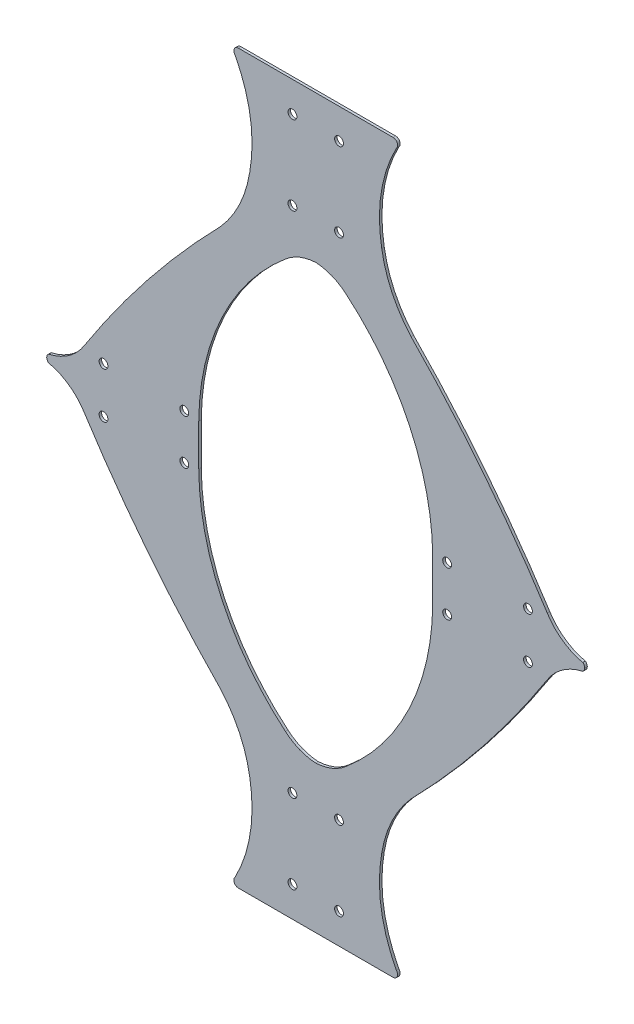
SolidWorks part; units mm, degrees
ref_plane "Front Plane" through (0, 0, 0) normal (0, 0, 1) x (1, 0, 0)
ref_plane "Top Plane" through (0, 0, 0) normal (0, 1, 0) x (1, 0, 0)
ref_plane "Right Plane" through (0, 0, 0) normal (1, 0, 0) x (0, 0, -1)
sketch "Model" plane through (0, 0, 0) normal (0, 0, 1) x (1, 0, 0)
  line B0 (293.8436, -56.5322) -> (293.8436, 0)
  line B1 (0, 914.4) -> (194.4798, 914.4)
  line B2 (293.8436, 56.5322) -> (293.8436, 0)
  line B3 (0, 914.4) -> (-194.4798, 914.4)
  line B4 (0, 545.0832) -> (0, 0) construction
  line B5 (0, 0) -> (293.8436, 0) construction
  arc B6 (239.6834, -503.1053) -> (187.9198, -583.3951) centre (465.825, -705.7322) ccw
  arc B7 (239.6834, -503.1053) -> (582.0374, -72.7477) centre (-1699.953, 1391.2476) ccw
  arc B8 (671.3071, -9.5736) -> (582.0374, -72.7477) centre (702.2766, -147.9952) ccw
  arc B9 (671.3071, -9.5736) -> (676.2743, 0) centre (664.8452, -0.1455) ccw
  arc B10 (101.6984, -491.6043) -> (294.1166, -52.0761) centre (-316.104, -46.8144) ccw
  circle B11 centre (330.3561, -56.5322) radius 11.1125
  circle B12 centre (533.5906, -57.7678) radius 11.1125
  arc B13 (202.9832, 895.3321) -> (194.4798, 914.4) centre (194.4798, 902.97) ccw
  arc B14 (202.9832, 895.3321) -> (165.892, 658.247) centre (527.5303, 723.1138) ccw
  arc B15 (165.9389, 658.1298) -> (239.6834, 503.1053) centre (465.825, 705.7322) ccw
  arc B16 (582.0374, 72.7477) -> (239.6834, 503.1053) centre (-1699.953, -1391.2476) ccw
  arc B17 (582.0374, 72.7477) -> (671.3071, 9.5736) centre (702.2766, 147.9952) ccw
  arc B18 (676.2743, 0) -> (671.3071, 9.5736) centre (664.8452, 0.1455) ccw
  arc B19 (294.1166, 52.0761) -> (76.1318, 514.3055) centre (-316.104, 46.8144) ccw
  arc B20 (76.1318, 514.3055) -> (0, 545.0832) centre (-7, 418.2194) ccw
  circle B21 centre (58.5418, 838.2689) radius 11.1125
  circle B22 centre (330.3561, 56.5322) radius 11.1125
  circle B23 centre (533.5906, 57.7678) radius 11.1125
  circle B24 centre (58.5418, 639.4053) radius 11.1125
  arc B25 (-194.4798, 914.4) -> (-202.9832, 895.3321) centre (-194.4798, 902.97) ccw
  arc B26 (-165.892, 658.247) -> (-202.9832, 895.3321) centre (-527.5303, 723.1138) ccw
  arc B27 (-187.9198, 583.3951) -> (-165.9389, 658.1298) centre (-465.825, 705.7322) ccw
  arc B28 (-76.1318, 514.3055) -> (-101.6984, 491.6043) centre (316.104, 46.8144) ccw
  arc B29 (0, 545.0832) -> (-76.1318, 514.3055) centre (7, 418.2194) ccw
  circle B30 centre (-58.5418, 838.2689) radius 11.1125
  circle B31 centre (-58.5418, 639.4053) radius 11.1125
  line B32 (-293.8436, 56.5322) -> (-293.8436, 0)
  line B33 (0, -914.4) -> (-194.4798, -914.4)
  line B34 (-293.8436, -56.5322) -> (-293.8436, 0)
  line B35 (0, -914.4) -> (194.4798, -914.4)
  line B36 (0, -545.0832) -> (0, 0) construction
  line B37 (0, 0) -> (-293.8436, 0) construction
  arc B38 (-239.6834, 503.1053) -> (-187.9198, 583.3951) centre (-465.825, 705.7322) ccw
  arc B39 (-239.6834, 503.1053) -> (-582.0374, 72.7477) centre (1699.953, -1391.2476) ccw
  arc B40 (-671.3071, 9.5736) -> (-582.0374, 72.7477) centre (-702.2766, 147.9952) ccw
  arc B41 (-671.3071, 9.5736) -> (-676.2743, 0) centre (-664.8452, 0.1455) ccw
  arc B42 (-101.6984, 491.6043) -> (-294.1166, 52.0761) centre (316.104, 46.8144) ccw
  circle B43 centre (-330.3561, 56.5322) radius 11.1125
  circle B44 centre (-533.5906, 57.7678) radius 11.1125
  arc B45 (-202.9832, -895.3321) -> (-194.4798, -914.4) centre (-194.4798, -902.97) ccw
  arc B46 (-202.9832, -895.3321) -> (-165.892, -658.247) centre (-527.5303, -723.1138) ccw
  arc B47 (-165.9389, -658.1298) -> (-239.6834, -503.1053) centre (-465.825, -705.7322) ccw
  arc B48 (-582.0374, -72.7477) -> (-239.6834, -503.1053) centre (1699.953, 1391.2476) ccw
  arc B49 (-582.0374, -72.7477) -> (-671.3071, -9.5736) centre (-702.2766, -147.9952) ccw
  arc B50 (-676.2743, 0) -> (-671.3071, -9.5736) centre (-664.8452, -0.1455) ccw
  arc B51 (-294.1166, -52.0761) -> (-76.1318, -514.3055) centre (316.104, -46.8144) ccw
  arc B52 (-76.1318, -514.3055) -> (0, -545.0832) centre (7, -418.2194) ccw
  circle B53 centre (-58.5418, -838.2689) radius 11.1125
  circle B54 centre (-330.3561, -56.5322) radius 11.1125
  circle B55 centre (-533.5906, -57.7678) radius 11.1125
  circle B56 centre (-58.5418, -639.4053) radius 11.1125
  arc B57 (194.4798, -914.4) -> (202.9832, -895.3321) centre (194.4798, -902.97) ccw
  arc B58 (165.892, -658.247) -> (202.9832, -895.3321) centre (527.5303, -723.1138) ccw
  arc B59 (187.9198, -583.3951) -> (165.9389, -658.1298) centre (465.825, -705.7322) ccw
  arc B60 (76.1318, -514.3055) -> (101.6984, -491.6043) centre (-316.104, -46.8144) ccw
  arc B61 (0, -545.0832) -> (76.1318, -514.3055) centre (-7, -418.2194) ccw
  circle B62 centre (58.5418, -838.2689) radius 11.1125
  circle B63 centre (58.5418, -639.4053) radius 11.1125
sketch_block_instance "Block1-1"
sketch_block "Block1"
sketch_block_instance "Block1-2"
sketch "Sketch2" plane through (0, 0, 0) normal (0, 0, 1) x (1, 0, 0)
  line L0 (0, 914.4) -> (-194.4798, 914.4) construction
  line L1 (0, 914.4) -> (194.4798, 914.4) construction
  line L2 (0, -914.4) -> (-194.4798, -914.4) construction
  line L3 (0, -914.4) -> (194.4798, -914.4) construction
  line L4 (0, 914.4) -> (-194.4798, 914.4)
  line L5 (0, 914.4) -> (194.4798, 914.4)
  line L6 (0, -914.4) -> (-194.4798, -914.4)
  line L7 (0, -914.4) -> (194.4798, -914.4)
  line L8 (294.1166, 52.0761) -> (294.1166, -52.0761)
  line L9 (-294.1166, -52.0761) -> (-294.1166, 52.0761)
  line L10 (-165.9389, 658.1298) -> (-165.892, 658.247)
  line L11 (165.892, 658.247) -> (165.9389, 658.1298)
  line L12 (165.892, -658.247) -> (165.9389, -658.1298)
  line L13 (-165.892, -658.247) -> (-165.9389, -658.1298)
  arc A0 (582.0374, 72.7477) -> (239.6834, 503.1053) centre (-1699.953, -1391.2476) ccw construction
  arc A1 (165.9389, 658.1298) -> (239.6834, 503.1053) centre (465.825, 705.7322) ccw construction
  arc A2 (202.9832, 895.3321) -> (165.892, 658.247) centre (527.5303, 723.1138) ccw construction
  arc A3 (202.9832, 895.3321) -> (194.4798, 914.4) centre (194.4798, 902.97) ccw construction
  arc A4 (-194.4798, 914.4) -> (-202.9832, 895.3321) centre (-194.4798, 902.97) ccw construction
  arc A5 (-165.892, 658.247) -> (-202.9832, 895.3321) centre (-527.5303, 723.1138) ccw construction
  arc A6 (-187.9198, 583.3951) -> (-165.9389, 658.1298) centre (-465.825, 705.7322) ccw construction
  arc A7 (-239.6834, 503.1053) -> (-187.9198, 583.3951) centre (-465.825, 705.7322) ccw construction
  arc A8 (-239.6834, 503.1053) -> (-582.0374, 72.7477) centre (1699.953, -1391.2476) ccw construction
  arc A9 (-671.3071, 9.5736) -> (-582.0374, 72.7477) centre (-702.2766, 147.9952) ccw construction
  arc A10 (-671.3071, 9.5736) -> (-676.2743, 0) centre (-664.8452, 0.1455) ccw construction
  arc A11 (-676.2743, 0) -> (-671.3071, -9.5736) centre (-664.8452, -0.1455) ccw construction
  arc A12 (-582.0374, -72.7477) -> (-671.3071, -9.5736) centre (-702.2766, -147.9952) ccw construction
  arc A13 (-582.0374, -72.7477) -> (-239.6834, -503.1053) centre (1699.953, 1391.2476) ccw construction
  arc A14 (-165.9389, -658.1298) -> (-239.6834, -503.1053) centre (-465.825, -705.7322) ccw construction
  arc A15 (-202.9832, -895.3321) -> (-165.892, -658.247) centre (-527.5303, -723.1138) ccw construction
  arc A16 (-202.9832, -895.3321) -> (-194.4798, -914.4) centre (-194.4798, -902.97) ccw construction
  arc A17 (194.4798, -914.4) -> (202.9832, -895.3321) centre (194.4798, -902.97) ccw construction
  arc A18 (165.892, -658.247) -> (202.9832, -895.3321) centre (527.5303, -723.1138) ccw construction
  arc A19 (187.9198, -583.3951) -> (165.9389, -658.1298) centre (465.825, -705.7322) ccw construction
  arc A20 (239.6834, -503.1053) -> (187.9198, -583.3951) centre (465.825, -705.7322) ccw construction
  arc A21 (239.6834, -503.1053) -> (582.0374, -72.7477) centre (-1699.953, 1391.2476) ccw construction
  arc A22 (582.0374, 72.7477) -> (671.3071, 9.5736) centre (702.2766, 147.9952) ccw construction
  arc A23 (676.2743, 0) -> (671.3071, 9.5736) centre (664.8452, 0.1455) ccw construction
  arc A24 (671.3071, -9.5736) -> (676.2743, 0) centre (664.8452, -0.1455) ccw construction
  arc A25 (671.3071, -9.5736) -> (582.0374, -72.7477) centre (702.2766, -147.9952) ccw construction
  arc A26 (-294.1166, -52.0761) -> (-76.1318, -514.3055) centre (316.104, -46.8144) ccw construction
  arc A27 (-101.6984, 491.6043) -> (-294.1166, 52.0761) centre (316.104, 46.8144) ccw construction
  arc A28 (-76.1318, 514.3055) -> (-101.6984, 491.6043) centre (316.104, 46.8144) ccw construction
  arc A29 (0, 545.0832) -> (-76.1318, 514.3055) centre (7, 418.2194) ccw construction
  arc A30 (76.1318, 514.3055) -> (0, 545.0832) centre (-7, 418.2194) ccw construction
  arc A31 (294.1166, 52.0761) -> (76.1318, 514.3055) centre (-316.104, 46.8144) ccw construction
  arc A32 (101.6984, -491.6043) -> (294.1166, -52.0761) centre (-316.104, -46.8144) ccw construction
  arc A33 (0, -545.0832) -> (76.1318, -514.3055) centre (-7, -418.2194) ccw construction
  arc A34 (-76.1318, -514.3055) -> (0, -545.0832) centre (7, -418.2194) ccw construction
  arc A35 (76.1318, -514.3055) -> (101.6984, -491.6043) centre (-316.104, -46.8144) ccw construction
  circle A36 centre (-58.5418, -639.4053) radius 11.1125 construction
  circle A37 centre (-58.5418, -838.2689) radius 11.1125 construction
  circle A38 centre (58.5418, -838.2689) radius 11.1125 construction
  circle A39 centre (58.5418, -639.4053) radius 11.1125 construction
  circle A40 centre (533.5906, -57.7678) radius 11.1125 construction
  circle A41 centre (330.3561, -56.5322) radius 11.1125 construction
  circle A42 centre (330.3561, 56.5322) radius 11.1125 construction
  circle A43 centre (533.5906, 57.7678) radius 11.1125 construction
  circle A44 centre (58.5418, 838.2689) radius 11.1125 construction
  circle A45 centre (-58.5418, 838.2689) radius 11.1125 construction
  circle A46 centre (-58.5418, 639.4053) radius 11.1125 construction
  circle A47 centre (58.5418, 639.4053) radius 11.1125 construction
  circle A48 centre (-330.3561, -56.5322) radius 11.1125 construction
  circle A49 centre (-330.3561, 56.5322) radius 11.1125 construction
  circle A50 centre (-533.5906, 57.7678) radius 11.1125 construction
  circle A51 centre (-533.5906, -57.7678) radius 11.1125 construction
  arc A52 (582.0374, 72.7477) -> (239.6834, 503.1053) centre (-1699.953, -1391.2476) ccw
  arc A53 (165.9389, 658.1298) -> (239.6834, 503.1053) centre (465.825, 705.7322) ccw
  arc A54 (202.9832, 895.3321) -> (165.892, 658.247) centre (527.5303, 723.1138) ccw
  arc A55 (202.9832, 895.3321) -> (194.4798, 914.4) centre (194.4798, 902.97) ccw
  arc A56 (-194.4798, 914.4) -> (-202.9832, 895.3321) centre (-194.4798, 902.97) ccw
  arc A57 (-165.892, 658.247) -> (-202.9832, 895.3321) centre (-527.5303, 723.1138) ccw
  arc A58 (-187.9198, 583.3951) -> (-165.9389, 658.1298) centre (-465.825, 705.7322) ccw
  arc A59 (-239.6834, 503.1053) -> (-187.9198, 583.3951) centre (-465.825, 705.7322) ccw
  arc A60 (-239.6834, 503.1053) -> (-582.0374, 72.7477) centre (1699.953, -1391.2476) ccw
  arc A61 (-671.3071, 9.5736) -> (-582.0374, 72.7477) centre (-702.2766, 147.9952) ccw
  arc A62 (-671.3071, 9.5736) -> (-676.2743, 0) centre (-664.8452, 0.1455) ccw
  arc A63 (-676.2743, 0) -> (-671.3071, -9.5736) centre (-664.8452, -0.1455) ccw
  arc A64 (-582.0374, -72.7477) -> (-671.3071, -9.5736) centre (-702.2766, -147.9952) ccw
  arc A65 (-582.0374, -72.7477) -> (-239.6834, -503.1053) centre (1699.953, 1391.2476) ccw
  arc A66 (-165.9389, -658.1298) -> (-239.6834, -503.1053) centre (-465.825, -705.7322) ccw
  arc A67 (-202.9832, -895.3321) -> (-165.892, -658.247) centre (-527.5303, -723.1138) ccw
  arc A68 (-202.9832, -895.3321) -> (-194.4798, -914.4) centre (-194.4798, -902.97) ccw
  arc A69 (194.4798, -914.4) -> (202.9832, -895.3321) centre (194.4798, -902.97) ccw
  arc A70 (165.892, -658.247) -> (202.9832, -895.3321) centre (527.5303, -723.1138) ccw
  arc A71 (187.9198, -583.3951) -> (165.9389, -658.1298) centre (465.825, -705.7322) ccw
  arc A72 (239.6834, -503.1053) -> (187.9198, -583.3951) centre (465.825, -705.7322) ccw
  arc A73 (239.6834, -503.1053) -> (582.0374, -72.7477) centre (-1699.953, 1391.2476) ccw
  arc A74 (582.0374, 72.7477) -> (671.3071, 9.5736) centre (702.2766, 147.9952) ccw
  arc A75 (676.2743, 0) -> (671.3071, 9.5736) centre (664.8452, 0.1455) ccw
  arc A76 (671.3071, -9.5736) -> (676.2743, 0) centre (664.8452, -0.1455) ccw
  arc A77 (671.3071, -9.5736) -> (582.0374, -72.7477) centre (702.2766, -147.9952) ccw
  arc A78 (-294.1166, -52.0761) -> (-76.1318, -514.3055) centre (316.104, -46.8144) ccw
  arc A79 (-101.6984, 491.6043) -> (-294.1166, 52.0761) centre (316.104, 46.8144) ccw
  arc A80 (-76.1318, 514.3055) -> (-101.6984, 491.6043) centre (316.104, 46.8144) ccw
  arc A81 (0, 545.0832) -> (-76.1318, 514.3055) centre (7, 418.2194) ccw
  arc A82 (76.1318, 514.3055) -> (0, 545.0832) centre (-7, 418.2194) ccw
  arc A83 (294.1166, 52.0761) -> (76.1318, 514.3055) centre (-316.104, 46.8144) ccw
  arc A84 (101.6984, -491.6043) -> (294.1166, -52.0761) centre (-316.104, -46.8144) ccw
  arc A85 (0, -545.0832) -> (76.1318, -514.3055) centre (-7, -418.2194) ccw
  arc A86 (-76.1318, -514.3055) -> (0, -545.0832) centre (7, -418.2194) ccw
  arc A87 (76.1318, -514.3055) -> (101.6984, -491.6043) centre (-316.104, -46.8144) ccw
  circle A88 centre (-58.5418, -639.4053) radius 11.1125
  circle A89 centre (-58.5418, -838.2689) radius 11.1125
  circle A90 centre (58.5418, -838.2689) radius 11.1125
  circle A91 centre (58.5418, -639.4053) radius 11.1125
  circle A92 centre (533.5906, -57.7678) radius 11.1125
  circle A93 centre (330.3561, -56.5322) radius 11.1125
  circle A94 centre (330.3561, 56.5322) radius 11.1125
  circle A95 centre (533.5906, 57.7678) radius 11.1125
  circle A96 centre (58.5418, 838.2689) radius 11.1125
  circle A97 centre (-58.5418, 838.2689) radius 11.1125
  circle A98 centre (-58.5418, 639.4053) radius 11.1125
  circle A99 centre (58.5418, 639.4053) radius 11.1125
  circle A100 centre (-330.3561, -56.5322) radius 11.1125
  circle A101 centre (-330.3561, 56.5322) radius 11.1125
  circle A102 centre (-533.5906, 57.7678) radius 11.1125
  circle A103 centre (-533.5906, -57.7678) radius 11.1125
extrude "Boss-Extrude1" add sketch "Sketch2" along normal blind 6.35
sketch "Sketch4" [suppressed] plane through (0, 0, 6.35) normal (0, 0, 1) x (1, 0, 0)
  line L0 (-563.1003, -101.854) -> (-563.1003, 101.854) construction
  line L1 (-563.1003, -101.854) -> (-563.1003, 101.854)
extrude "Cut-Extrude1" [suppressed] cut sketch "Sketch4" against normal through all and the other way through all
